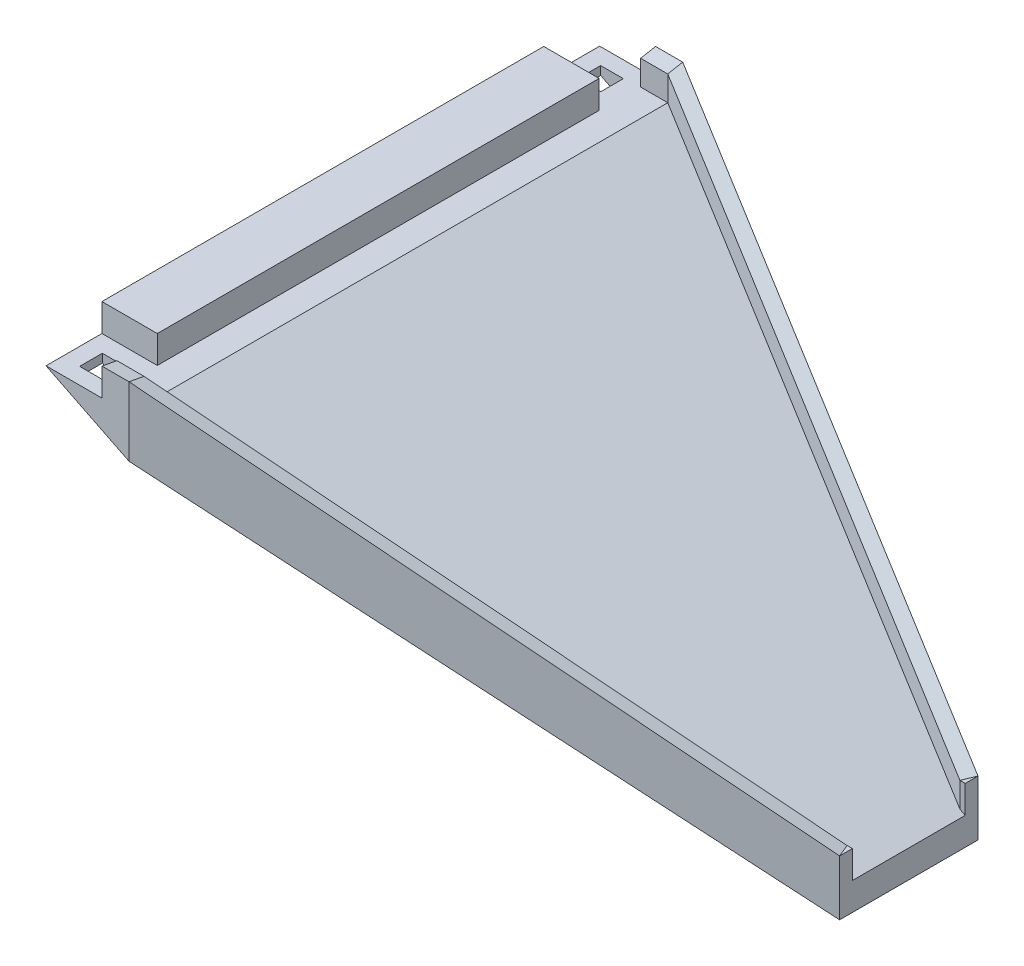
SolidWorks part; units mm, degrees
ref_plane "Front Plane" through (0, 0, 0) normal (0, 0, 1) x (1, 0, 0)
ref_plane "Top Plane" through (0, 0, 0) normal (0, 1, 0) x (1, 0, 0)
ref_plane "Right Plane" through (0, 0, 0) normal (1, 0, 0) x (0, 0, -1)
sketch "Croquis1" plane through (0, 0, 0) normal (0, 0, 1) x (1, 0, 0)
  line L2 (4.273, 100) -> (215.932, -5)
  line L4 (215.932, -5) -> (215.932, 5)
  line L5 (215.932, 5) -> (34.273, 100)
  line L6 (34.273, 100) -> (4.273, 100)
  point P1 (0, 0)
  point P3 (0, 98.358)
  point P4 (-2.5108, 99.7812)
  point P9 (0, 0)
  point P10 (0, 100)
  point P11 (207.011, 17.3959)
  point P12 (214.9145, 0)
  dimension "D1" = 30
  dimension "D2" = 10
  dimension "D5" = 100
  dimension "D6" = 205
extrude "Saliente-Extruir1" add sketch "Croquis1" along normal blind 200
sketch "Croquis2" plane through (0, 100, 0) normal (0, 1, 0) x (1, 0, 0)
  line L0 (34.273, 0) -> (4.273, 0) construction
  line L1 (4.273, -200) -> (4.273, 0) construction
  line L7 (10.523, -14.1) -> (18.723, -14.1)
  line L8 (10.523, -14.1) -> (10.523, -5.9)
  line L9 (10.523, -5.9) -> (18.723, -5.9)
  line L10 (18.723, -14.1) -> (18.723, -5.9)
  line L11 (10.523, -14.1) -> (18.723, -5.9) construction
  line L12 (10.523, -5.9) -> (18.723, -14.1) construction
  point P2 (22.8238, -10)
  point P16 (14.623, -10)
  dimension "D1" = 8.2
  dimension "D2" = 6.25
  dimension "D5" = 10
extrude "Cortar-Extruir1" cut sketch "Croquis2" against normal blind 200
sketch "Croquis8" plane through (0, 100, 0) normal (0, 1, 0) x (1, 0, 0)
  line L0 (34.273, 0) -> (215.932, -75)
  line L1 (215.932, -200) -> (215.932, 0) construction
  line L2 (215.932, -75) -> (215.932, -125)
  line L3 (215.932, -125) -> (34.273, -200)
  line L4 (34.273, -200) -> (215.932, -200)
  line L5 (215.932, -200) -> (215.932, -125)
  line L6 (215.932, -75) -> (215.932, 0)
  line L7 (215.932, 0) -> (34.273, 0)
  dimension "D1" = 50
extrude "Cortar-Extruir3" cut sketch "Croquis8" against normal through all contours L4 L5 L3 | L6 L7 L0
sketch "Croquis9" plane through (4.9912, 0, -12.0893) normal (0.3816, 0, -0.9243) x (-0.9243, 0, -0.3816)
  line L0 (-228.2117, 5) -> (-228.2117, 15)
  line L1 (-228.2117, 15) -> (-31.6793, 110)
  line L2 (-31.6793, 110) -> (-31.6793, 100)
  line L3 (-31.6793, 100) -> (-228.2117, 5)
  dimension "D1" = 10
extrude "Saliente-Extruir3" add sketch "Croquis9" against normal blind 5
ref_plane "Plano2" through (0, 0, 100) normal (0, 0, 1) x (1, 0, 0)
mirror "Simetría2" about plane through (0, 0, 100) normal (0, 0, 1) of "Saliente-Extruir3"
sketch "Croquis10" plane through (215.932, 0, 0) normal (1, 0, 0) x (0, 0, -1)
  line L0 (-75, -5) -> (-75, 5) construction
  line L1 (-125, 5) -> (-120.3784, 5)
  line L2 (-125, 5) -> (-125, 15)
  line L3 (-125, 15) -> (-120.3784, 15)
  line L4 (-120.3784, 5) -> (-120.3784, 15)
  line L5 (-79.6216, 15) -> (-75, 15)
  line L6 (-79.6216, 15) -> (-79.6216, 5)
  line L7 (-79.6216, 5) -> (-75, 5)
  line L8 (-75, 15) -> (-75, 5)
  line L9 (-125, 5) -> (-75, 5) construction
extrude "Saliente-Extruir4" add sketch "Croquis10" against normal up to next
sketch "Croquis11" plane through (0, 100, 0) normal (0, 1, 0) x (1, 0, 0)
  line L1 (4.273, -20.2) -> (24.273, -20.2)
  line L2 (4.273, -20.2) -> (4.273, -179.8)
  line L3 (4.273, -179.8) -> (24.273, -179.8)
  line L4 (24.273, -20.2) -> (24.273, -179.8)
  line L5 (4.273, -200) -> (4.273, 0) construction
  line L7 (34.273, 0) -> (4.273, 0) construction
  line L10 (34.273, -200) -> (4.273, -200) construction
  point P4 (7.4892, -20.2)
  point P6 (0, -179.8)
  dimension "D1" = 20.2
  dimension "D2" = 20
  dimension "D3" = 20.2
extrude "Saliente-Extruir6" add sketch "Croquis11" along normal blind 10
sketch "Croquis12" plane through (0, 100, 0) normal (0, 1, 0) x (1, 0, 0)
  line L0 (34.273, -200) -> (34.273, -194.5906)
  line L1 (34.273, -194.5906) -> (32.3649, -195.3784)
  line L2 (32.3649, -195.3784) -> (34.273, -200)
extrude "Cortar-Extruir4" cut sketch "Croquis12" along normal through all
mirror "Simetría3" about plane through (0, 0, 100) normal (0, 0, 1) of "Cortar-Extruir4"
sketch "Croquis13" plane through (215.932, 0, 0) normal (1, 0, 0) x (0, 0, -1)
  line L1 (-120.3784, 0) -> (-79.6216, 0)
  line L7 (-79.6216, 5) -> (-120.3784, 5)
  line L11 (-120.3784, 5) -> (-120.3784, 0)
  line L12 (-79.6216, 5) -> (-79.6216, 0)
extrude "Saliente-Extruir7" [suppressed] add sketch "Croquis13" along normal blind 10
sketch "Croquis14" [suppressed] plane through (0, 0, 79.6363) normal (0, 0, -1) x (-1, 0, 0)
  line L0 (-225.932, 0) -> (-215.932, 13.2281)
  line L1 (-215.932, 13.2281) -> (-225.932, 13.2281)
  line L2 (-225.932, 13.2281) -> (-225.932, 0)
extrude "Cortar-Extruir5" [suppressed] cut sketch "Croquis14" against normal through all
sketch "Croquis15" plane through (215.932, 0, 0) normal (1, 0, 0) x (0, 0, -1)
  line L1 (-79.6216, 15) -> (-75, 15)
  line L2 (-79.6216, 15) -> (-79.6216, 0)
  line L3 (-79.6216, 0) -> (-75, 0)
  line L4 (-75, 15) -> (-75, 0)
extrude "Saliente-Extruir8" [suppressed] add sketch "Croquis15" along normal blind 10
mirror "Simetría4" [suppressed] about plane through (0, 0, 100) normal (0, 0, 1)
mirror "Simetría5" about plane through (0, 0, 100) normal (0, 0, 1) of "Cortar-Extruir1"
ref_plane "Plano3" through (24.473, 0, 0) normal (-1, 0, 0) x (0, 0, 1)
sketch "Croquis17" plane through (24.473, 0, 0) normal (-1, 0, 0) x (0, 0, 1)
  line L0 (194.5906, 109.0022) -> (194.5906, 100)
  line L5 (194.5906, 100) -> (200, 100)
  line L6 (200, 100) -> (200, 110)
  line L7 (200, 110) -> (194.5906, 109.0022)
extrude "Saliente-Extruir10" add sketch "Croquis17" against normal up to next
mirror "Simetría6" about plane through (0, 0, 100) normal (0, 0, 1) of "Saliente-Extruir10"
